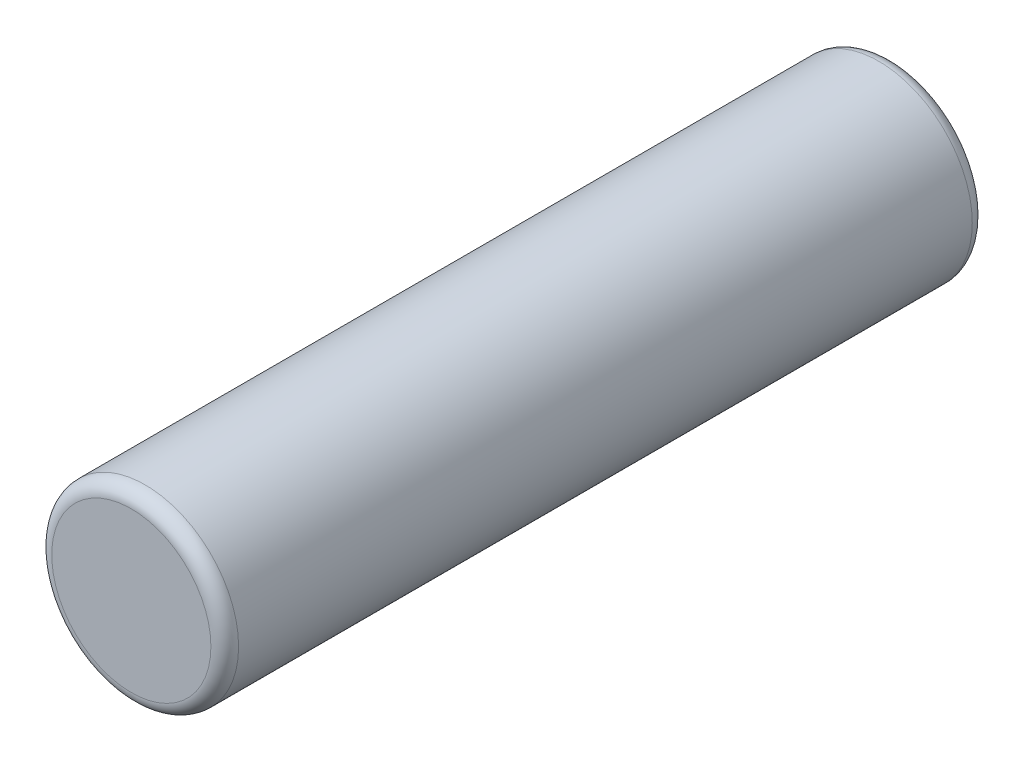
SolidWorks part; units mm, degrees
ref_plane "Front Plane" through (0, 0, 0) normal (0, 0, 1) x (1, 0, 0)
ref_plane "Top Plane" through (0, 0, 0) normal (0, 1, 0) x (1, 0, 0)
ref_plane "Right Plane" through (0, 0, 0) normal (1, 0, 0) x (0, 0, -1)
sketch "Sketch1" plane through (0, 0, 0) normal (0, 0, 1) x (1, 0, 0)
  circle A0 centre (0, 0) radius 13.5
  dimension "D1" = 27
extrude "Boss-Extrude1" add sketch "Sketch1" along normal blind 110
fillet "Fillet1" radius 2 1 edges at (13.5, 0, 110)
fillet "Fillet2" radius 2 1 edges at (13.5, 0, 0)
sketch "Sketch3" plane through (0, 0, 0) normal (1, 0, 0) x (0, 0, -1)
  line L0 (0, 0) -> (-110, 0) construction
  line L1 (-110, 11.5) -> (-110, -11.5) construction
  line L2 (-55, 0) -> (-55, -10.0675) construction
  point P5 (-55, 0)
